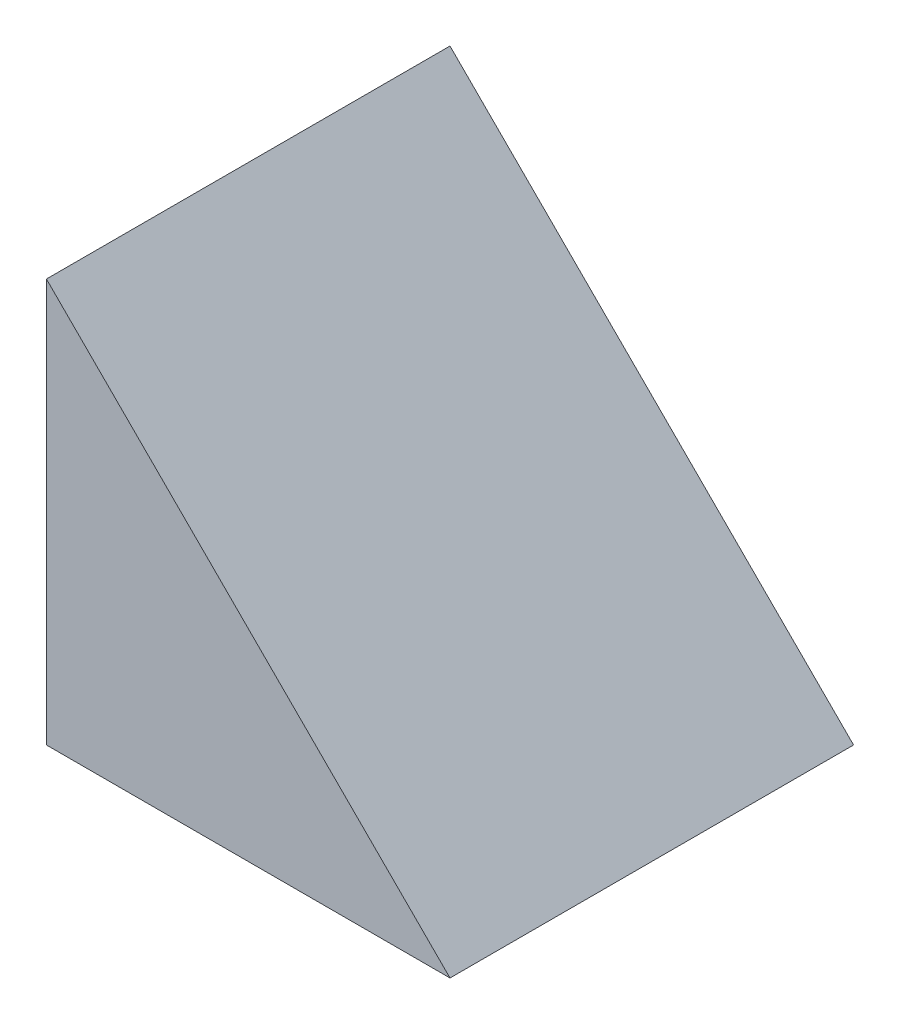
SolidWorks part; units mm, degrees
ref_plane "前视基准面" through (0, 0, 0) normal (0, 0, 1) x (1, 0, 0)
ref_plane "上视基准面" through (0, 0, 0) normal (0, 1, 0) x (1, 0, 0)
ref_plane "右视基准面" through (0, 0, 0) normal (1, 0, 0) x (0, 0, -1)
sketch "草图1" plane through (0, 0, 0) normal (0, 0, 1) x (1, 0, 0)
  line L0 (0, 0) -> (20, 0)
  line L1 (0, 0) -> (0, 20)
  line L2 (0, 20) -> (20, 0)
  dimension "D1" = 20
  dimension "D2" = 20
extrude "凸台-拉伸1" add sketch "草图1" along normal blind 20
